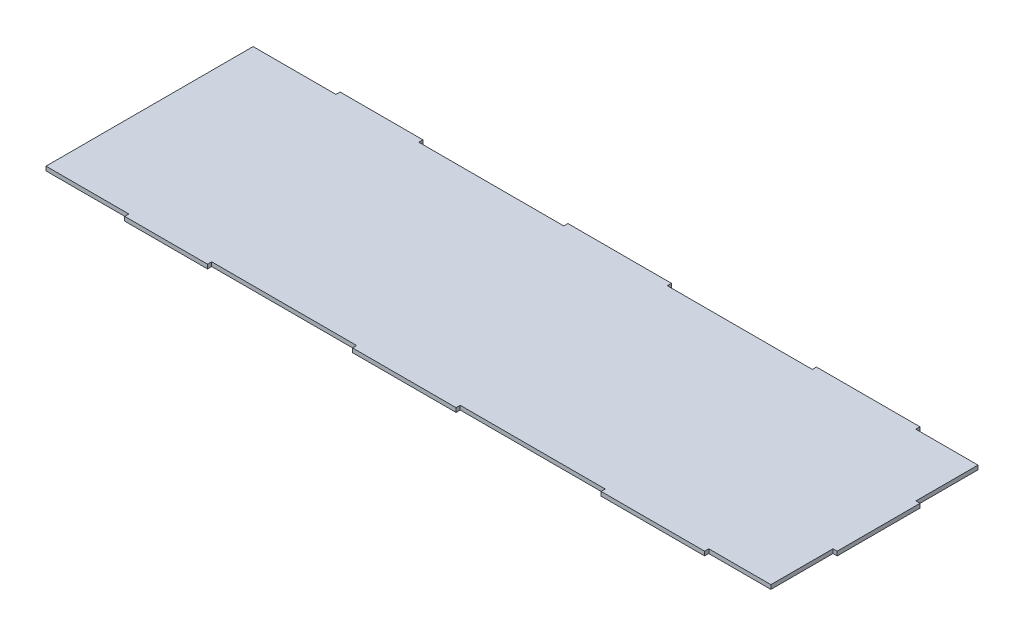
SolidWorks part; units mm, degrees
ref_plane "前视基准面" through (0, 0, 0) normal (0, 0, 1) x (1, 0, 0)
ref_plane "上视基准面" through (0, 0, 0) normal (0, 1, 0) x (1, 0, 0)
ref_plane "右视基准面" through (0, 0, 0) normal (1, 0, 0) x (0, 0, -1)
sketch "草图1" plane through (0, 0, 0) normal (0, 1, 0) x (1, 0, 0)
  line L0 (0, 50) -> (0, -50)
  line L1 (0, 50) -> (350, 50)
  line L2 (0, -50) -> (350, -50)
  line L3 (350, 50) -> (350, -50)
  line L4 (40, 52) -> (40, 50)
  line L5 (40, 52) -> (80, 52)
  line L6 (40, 50) -> (80, 50)
  line L7 (80, 52) -> (80, 50)
  line L8 (150, 52) -> (150, 50)
  line L9 (150, 52) -> (200, 52)
  line L10 (150, 50) -> (200, 50)
  line L11 (200, 52) -> (200, 50)
  line L12 (270, 52) -> (270, 50)
  line L13 (270, 52) -> (320, 52)
  line L14 (270, 50) -> (320, 50)
  line L15 (320, 52) -> (320, 50)
  line L16 (40, -50) -> (40, -52)
  line L17 (40, -50) -> (80, -50)
  line L18 (40, -52) -> (80, -52)
  line L19 (80, -50) -> (80, -52)
  line L20 (150, -50) -> (150, -52)
  line L21 (150, -50) -> (200, -50)
  line L22 (150, -52) -> (200, -52)
  line L23 (200, -50) -> (200, -52)
  line L24 (270, -50) -> (270, -52)
  line L25 (270, -50) -> (320, -50)
  line L26 (270, -52) -> (320, -52)
  line L27 (320, -50) -> (320, -52)
  point P0 (40, 52)
  point P3 (40, 50)
  point P4 (80, 52)
  point P5 (80, 50)
  point P6 (40, -50)
  point P7 (40, -52)
  point P8 (80, -50)
  point P11 (80, -52)
  point P12 (150, 50)
  point P13 (150, 52)
  point P14 (200, 50)
  point P15 (200, 52)
  point P16 (200, -50)
  point P17 (200, -52)
  point P18 (150, -50)
  point P19 (150, -52)
  point P20 (270, 50)
  point P21 (270, 52)
  point P22 (270, -50)
  point P23 (270, -52)
  point P24 (320, 50)
  point P25 (320, -52)
  point P26 (320, -50)
  point P27 (320, 52)
extrude "凸台-拉伸1" add sketch "草图1" along normal blind 2 contours L7 L5 L4 L1 | L19 L2 L16 L18 | L11 L9 L8 L1 | L23 L2 L20 L22 | L15 L13 L12 L1 | L27 L2 L24 L26 | L3 L1 L0 L2
sketch "草图2" plane through (0, 0, 0) normal (0, 1, 0) x (1, 0, 0)
  line L0 (350, 20) -> (352, 20)
  line L1 (350, 20) -> (350, -20)
  line L2 (352, 20) -> (352, -20)
  line L3 (350, -20) -> (352, -20)
  point P0 (352, 20)
  point P1 (350, 20)
  point P2 (350, -20)
  point P3 (352, -20)
  point P4 (0, 0)
extrude "凸台-拉伸2" add sketch "草图2" along normal blind 2 contours L1 L3 L2 L0
